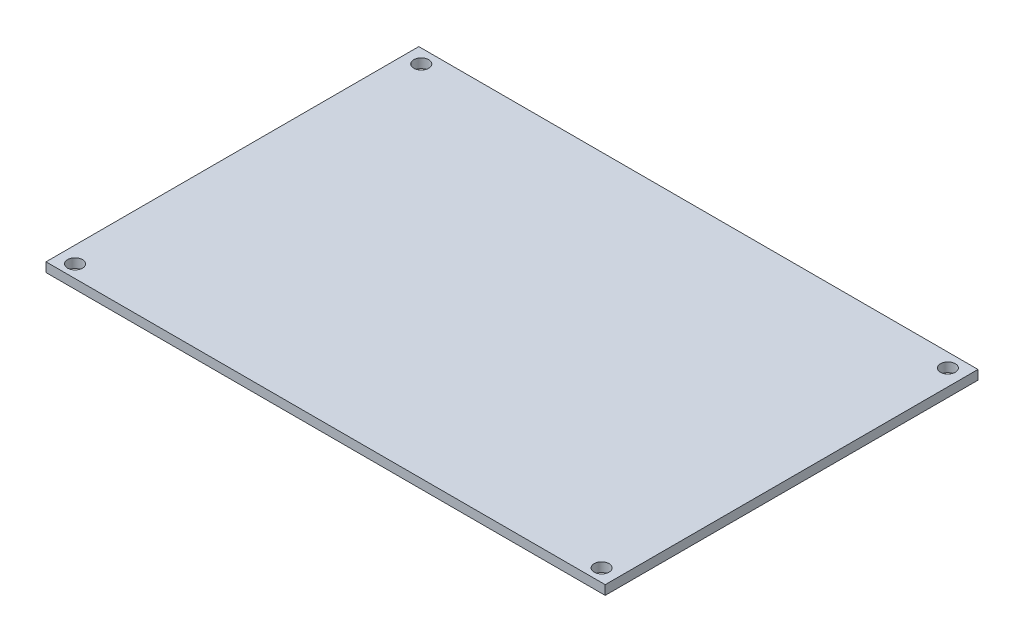
SolidWorks part; units mm, degrees
material "电源线路板"
ref_plane "前视基准面" through (0, 0, 0) normal (0, 0, 1) x (1, 0, 0)
ref_plane "上视基准面" through (0, 0, 0) normal (0, 1, 0) x (1, 0, 0)
ref_plane "右视基准面" through (0, 0, 0) normal (1, 0, 0) x (0, 0, -1)
other "Configuration Table"
sketch "草图1" plane through (0, 0, 0) normal (0, 1, 0) x (1, 0, 0)
  line L1 (-84.8842, 82.281) -> (35.1158, 82.281)
  line L2 (-84.8842, 82.281) -> (-84.8842, 2.281)
  line L3 (-84.8842, 2.281) -> (35.1158, 2.281)
  line L4 (35.1158, 82.281) -> (35.1158, 2.281)
  dimension "D1" = 120
  dimension "D2" = 80
extrude "凸台-拉伸1" add sketch "草图1" along normal blind 2
sketch "草图2" plane through (0, 2, 0) normal (0, 1, 0) x (1, 0, 0)
  circle A0 centre (-81.3872, 79.3135) radius 1.6
  circle A1 centre (-81.3872, 5.0135) radius 1.6
  circle A2 centre (31.6128, 5.0135) radius 1.6
  circle A3 centre (31.6128, 79.3135) radius 1.6
  point P8 (-76.1857, 76.3234)
  point P9 (0, 0)
  point P10 (0, 0)
  point P11 (-81.7224, 79.1783)
  point P12 (-81.766, 78.8338)
  point P13 (0, 0)
  point P14 (-81.3872, 79.3135)
  dimension "D1" = 3.2
  dimension "D2" = 3.2
  dimension "D3" = 3.2
  dimension "D4" = 3.2
  dimension "D5" = 113
  dimension "D6" = 74.3
  dimension "D7" = 74.3
  dimension "D8" = 113
extrude "切除-拉伸1" cut sketch "草图2" against normal blind 10
